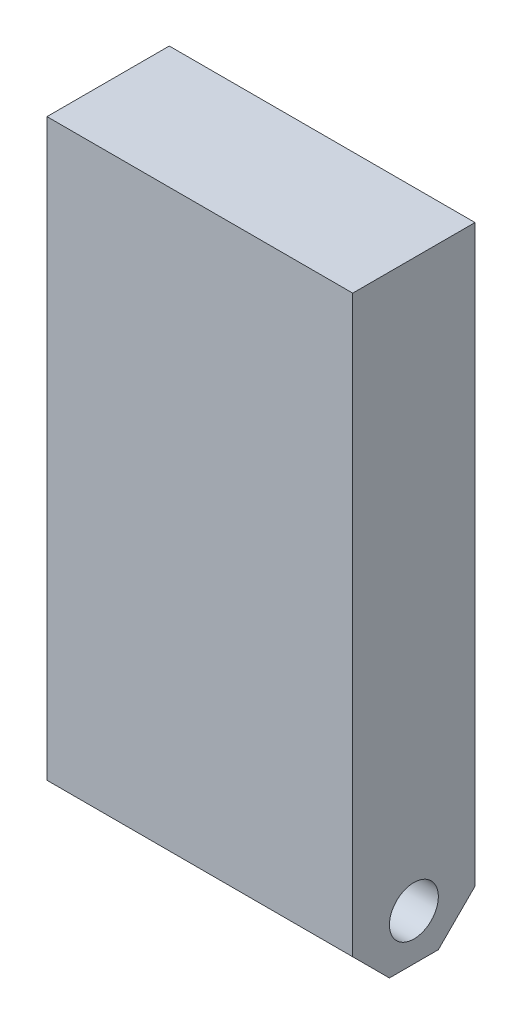
SolidWorks part; units mm, degrees
material "1060 合金"
ref_plane "前视基准面" through (0, 0, 0) normal (0, 0, 1) x (1, 0, 0)
ref_plane "上视基准面" through (0, 0, 0) normal (0, 1, 0) x (1, 0, 0)
ref_plane "右视基准面" through (0, 0, 0) normal (1, 0, 0) x (0, 0, -1)
sketch "草图1" plane through (0, 0, 0) normal (0, 0, 1) x (1, 0, 0)
  line L0 (0, 55.0293) -> (0, 0) construction
  line L1 (0, 0) -> (72.0409, 0) construction
  line L2 (25, 0) -> (-25, 0)
  line L3 (25, 0) -> (25, 100)
  line L4 (25, 100) -> (-25, 100)
  line L5 (-25, 0) -> (-25, 100)
  dimension "D1" = 50
  dimension "D2" = 100
extrude "凸台-拉伸1" add sketch "草图1" along normal mid plane 20
sketch "草图2" plane through (-25, 0, 0) normal (-1, 0, 0) x (0, 0, 1)
  circle A0 centre (0, 7.5226) radius 4
  dimension "D1" = 8
extrude "切除-拉伸1" cut sketch "草图2" against normal through all
chamfer "倒角1" distance 6 angle 45 2 edges at (0, 0, 10) (0, 0, -10)
